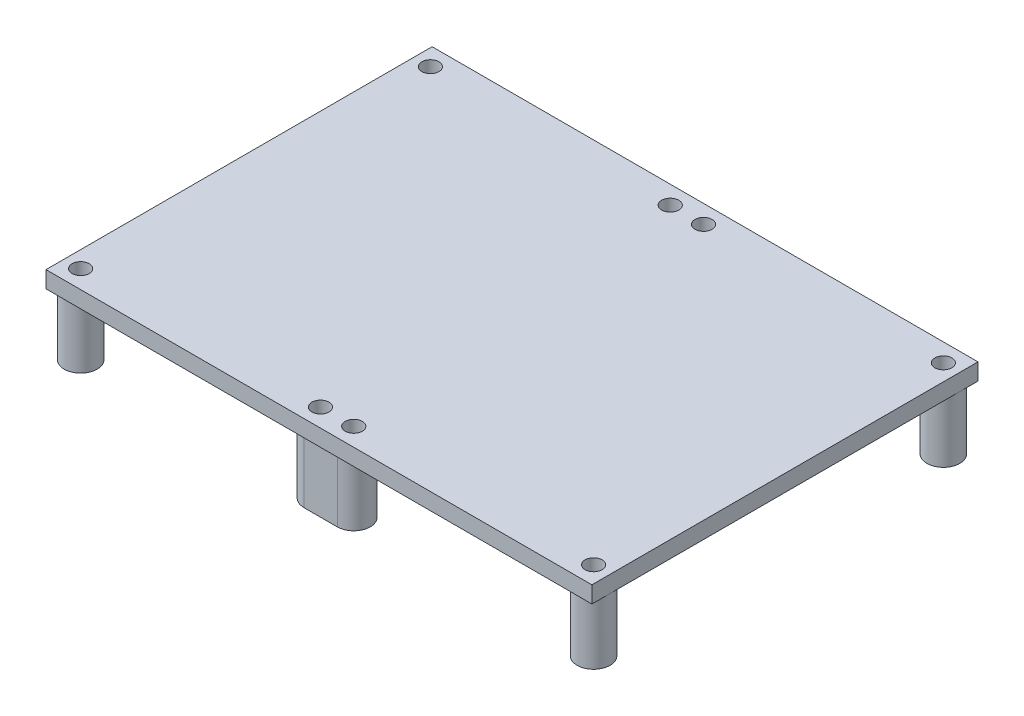
SolidWorks part; units mm, degrees
material "PET"
ref_plane "Front Plane" through (0, 0, 0) normal (0, 0, 1) x (1, 0, 0)
ref_plane "Top Plane" through (0, 0, 0) normal (0, 1, 0) x (1, 0, 0)
ref_plane "Right Plane" through (0, 0, 0) normal (1, 0, 0) x (0, 0, -1)
sketch "Sketch1" plane through (0, 0, 0) normal (0, 1, 0) x (1, 0, 0)
  line L1 (-0.035, 36.805) -> (-52.035, 36.805)
  line L2 (-0.035, 36.805) -> (-0.035, -36.805) construction
  line L3 (-0.035, -36.805) -> (-52.035, -36.805)
  line L4 (-52.035, 36.805) -> (-52.035, -36.805)
  line L5 (-0.035, 36.805) -> (-52.035, -36.805) construction
  line L6 (-0.035, -36.805) -> (-52.035, 36.805) construction
  line L7 (-0.035, 36.805) -> (0, 36.805)
  line L8 (0, 36.805) -> (0, -36.805)
  line L9 (-48.895, -33.34) -> (-3.175, -33.34) construction
  line L10 (-48.895, -33.34) -> (-48.895, 33.34) construction
  line L11 (-48.895, 33.34) -> (-3.175, 33.34) construction
  line L12 (-3.175, -33.34) -> (-3.175, 33.34) construction
  line L13 (-48.895, -33.34) -> (-3.175, 33.34) construction
  line L14 (-48.895, 33.34) -> (-3.175, -33.34) construction
  line L15 (0, -36.805) -> (-0.035, -36.805)
  point P0 (-26.035, 0)
  point P9 (-26.035, 0)
  dimension "D1" = 52
  dimension "D2" = 73.61
  dimension "D3" = 66.68
  dimension "D4" = 45.72
  dimension "D5" = 3.175
extrude "Boss-Extrude1" add sketch "Sketch1" against normal blind 3.175
sketch "Sketch2" plane through (0, 0, 0) normal (0, 1, 0) x (1, 0, 0)
  line L0 (-52.035, 36.805) -> (-52.035, -36.805) construction
  line L2 (0, 36.805) -> (0, -36.805) construction
  line L3 (-3.175, 36.48) -> (0, 36.48)
  line L4 (-3.175, 36.48) -> (-3.175, 30.2)
  line L5 (-3.175, 30.2) -> (0, 30.2)
  line L6 (0, 36.48) -> (0, 30.2)
  line L7 (-3.175, -30.2) -> (0, -30.2)
  line L8 (-3.175, -30.2) -> (-3.175, -36.48)
  line L9 (-3.175, -36.48) -> (0, -36.48)
  line L10 (0, -30.2) -> (0, -36.48)
  circle A0 centre (-48.895, 33.34) radius 3.14
  circle A1 centre (-3.175, 33.34) radius 3.14
  circle A2 centre (-48.895, -33.34) radius 3.14
  circle A3 centre (-3.175, -33.34) radius 3.14
  point P14 (0, 0)
  point P15 (0, 36.48)
  point P24 (-3.14, -40.0474)
  point P25 (-3.14, -36.48)
  point P26 (-3.14, 28.396)
  point P27 (0, 30.2)
  point P28 (-0.003, 36.48)
  point P30 (0, 0)
extrude "Boss-Extrude2" add sketch "Sketch2" against normal blind 15.0412
hole_wizard "#4 Clearance Hole1" positions "Sketch3" profile "Sketch4" hole size "#4" standard "ANSI Inch"
sketch "Sketch3" plane through (0, -15.0412, 0) normal (0, -1, 0) x (-1, 0, 0)
  arc A0 (3.175, 30.2) -> (3.175, 36.48) centre (3.175, 33.34) ccw construction
  point P0 (48.895, 33.34)
  point P3 (3.175, 33.34)
  point P5 (3.175, -33.34)
  point P8 (48.895, -33.34)
  point P12 (0, 0)
  point P13 (0, 0)
sketch "Sketch4" plane through (-48.895, -15.0412, -33.34) normal (1, 0, 0) x (0, 0, -1)
  line L0 (0, 0) -> (0, 26.3806)
  line L1 (0, 26.3806) -> (1.6319, 25.4)
  line L2 (1.6319, 25.4) -> (1.6319, 0)
  line L5 (1.6319, 0) -> (0, 0)
  line L10 (0, 26.3806) -> (-1.632, 25.4) construction
  line L11 (0, -6.35) -> (0, 107.95) construction
  dimension "Hole Dia." = 3.2639
  dimension "Hole Depth" = 25.4
  dimension "Drill Angle" = 118
mirror "Mirror1" about plane through (0, -3.175, 0) normal (-1, 0, 0) of bodies 103
